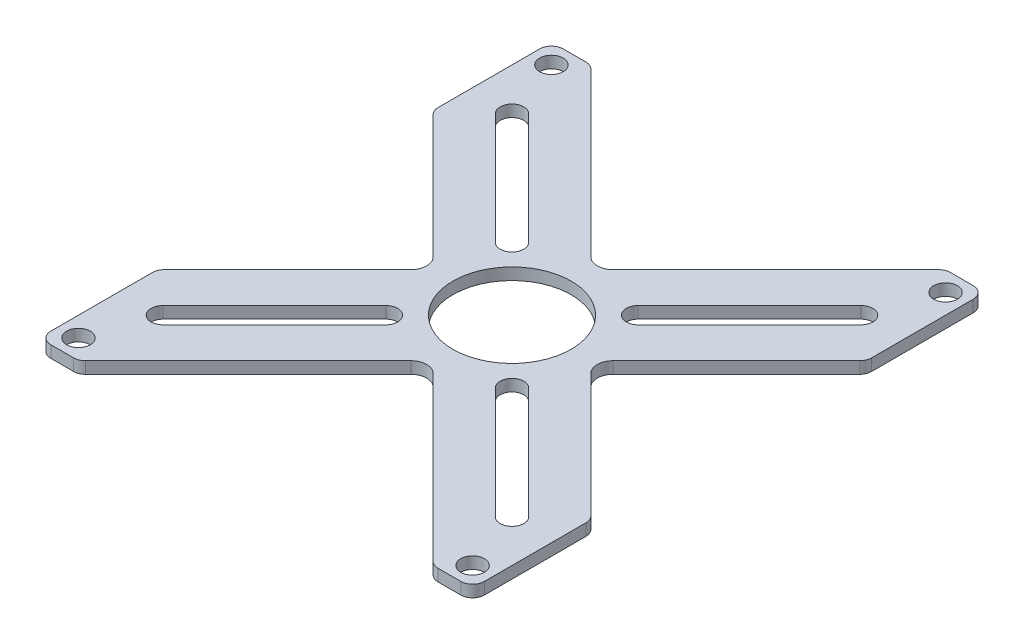
SolidWorks part; units mm, degrees
ref_plane "前视基准面" through (0, 0, 0) normal (0, 0, 1) x (1, 0, 0)
ref_plane "上视基准面" through (0, 0, 0) normal (0, 1, 0) x (1, 0, 0)
ref_plane "右视基准面" through (0, 0, 0) normal (1, 0, 0) x (0, 0, -1)
other "Configuration Table"
sketch "草图1" plane through (0, 0, 0) normal (0, 1, 0) x (1, 0, 0)
  line L1 (-27.5, -32.5) -> (27.5, -32.5)
  line L2 (-27.5, -32.5) -> (-27.5, 32.5)
  line L3 (-27.5, 32.5) -> (27.5, 32.5)
  line L4 (27.5, -32.5) -> (27.5, 32.5)
  line L5 (0, 32.5) -> (0, -32.5) construction
  line L6 (-27.5, 0) -> (27.5, 0) construction
  circle A0 centre (-25, 30) radius 1.5
  circle A1 centre (25, 30) radius 1.5
  circle A2 centre (25, -30) radius 1.5
  circle A3 centre (-25, -30) radius 1.5
  point P0 (0, 0)
  dimension "D3" = 3
  dimension "D4" = 3
  dimension "D5" = 3
  dimension "D6" = 3
  dimension "D7" = 25
  dimension "D8" = 25
  dimension "D9" = 30
  dimension "D10" = 30
  dimension "D11" = 25
  dimension "D12" = 25
  dimension "D13" = 30
  dimension "D14" = 30
  dimension "D1" = 65
  dimension "D2" = 55
extrude "凸台-拉伸1" add sketch "草图1" along normal blind 1.5
sketch "草图2" plane through (0, 1.5, 0) normal (0, 1, 0) x (1, 0, 0)
  line L0 (-22.1421, 22.1421) -> (-8, 8) construction
  line L1 (-21.0815, 23.2028) -> (-6.9393, 9.0607)
  line L2 (-23.2028, 21.0815) -> (-9.0607, 6.9393)
  line L3 (-27.5, 32.5) -> (-27.5, -32.5) construction
  line L4 (21.0815, 23.2028) -> (6.9393, 9.0607)
  line L5 (23.2028, 21.0815) -> (9.0607, 6.9393)
  line L6 (22.1421, 22.1421) -> (8, 8) construction
  line L7 (23.2028, -21.0815) -> (9.0607, -6.9393)
  line L8 (21.0815, -23.2028) -> (6.9393, -9.0607)
  line L9 (22.1421, -22.1421) -> (8, -8) construction
  line L10 (-21.0815, -23.2028) -> (-6.9393, -9.0607)
  line L11 (-23.2028, -21.0815) -> (-9.0607, -6.9393)
  line L12 (-22.1421, -22.1421) -> (-8, -8) construction
  arc A1 (-21.0815, 23.2028) -> (-23.2028, 21.0815) centre (-22.1421, 22.1421) ccw
  arc A2 (-9.0607, 6.9393) -> (-6.9393, 9.0607) centre (-8, 8) ccw
  arc A3 (23.2028, 21.0815) -> (21.0815, 23.2028) centre (22.1421, 22.1421) ccw
  arc A4 (6.9393, 9.0607) -> (9.0607, 6.9393) centre (8, 8) ccw
  arc A5 (21.0815, -23.2028) -> (23.2028, -21.0815) centre (22.1421, -22.1421) ccw
  arc A6 (9.0607, -6.9393) -> (6.9393, -9.0607) centre (8, -8) ccw
  arc A7 (-23.2028, -21.0815) -> (-21.0815, -23.2028) centre (-22.1421, -22.1421) ccw
  arc A8 (-6.9393, -9.0607) -> (-9.0607, -6.9393) centre (-8, -8) ccw
  point P2 (-15.0711, 15.0711)
  point P15 (15.0711, 15.0711)
  point P22 (15.0711, -15.0711)
  point P29 (-15.0711, -15.0711)
  point P34 (0, 0)
  dimension "D4" = 8
  dimension "D5" = 8
  dimension "D1" = 3
  dimension "D2" = 45
  dimension "D3" = 20
  dimension "D6" = 4
extrude "切除-拉伸1" cut sketch "草图2" against normal blind 1.5
sketch "草图3" plane through (0, 1.5, 0) normal (0, 1, 0) x (1, 0, 0)
  line L0 (-22.5, 32.5) -> (0, 10)
  line L1 (27.5, 32.5) -> (-27.5, 32.5) construction
  line L2 (0, 10) -> (22.5, 32.5)
  line L3 (22.5, 32.5) -> (-22.5, 32.5)
  line L4 (-27.5, 17.5) -> (-10, 0)
  line L5 (-27.5, 32.5) -> (-27.5, -32.5) construction
  line L6 (-10, 0) -> (-27.5, -17.5)
  line L7 (-27.5, -17.5) -> (-27.5, 17.5)
  line L8 (-1000, 0) -> (49000, 0) construction
  line L9 (0, -1000) -> (0, 49000) construction
  line L10 (10, 0) -> (27.5, -17.5)
  line L11 (27.5, 17.5) -> (10, 0)
  line L12 (27.5, -17.5) -> (27.5, 17.5)
  line L13 (0, -10) -> (22.5, -32.5)
  line L14 (-22.5, -32.5) -> (0, -10)
  line L15 (22.5, -32.5) -> (-22.5, -32.5)
  circle A0 centre (0, 0) radius 7.5
  dimension "D6" = 15
  dimension "D1" = 45
  dimension "D2" = 45
  dimension "D3" = 0
  dimension "D4" = 0
  dimension "D5" = 35
extrude "切除-拉伸2" cut sketch "草图3" against normal through all
fillet "圆角1" radius 2 4 edges at (0, 0.75, -10) (0, 0.75, 10) (10, 0.75, 0) (-10, 0.75, 0)
fillet "圆角2" radius 1.5 12 edges at (-27.5, 0.75, 17.5) (-27.5, 0.75, 32.5) (-22.5, 0.75, 32.5) (-27.5, 0.75, -17.5) (-27.5, 0.75, -32.5) (-22.5, 0.75, -32.5) (22.5, 0.75, -32.5) (27.5, 0.75, -32.5) (27.5, 0.75, -17.5) (27.5, 0.75, 17.5) (27.5, 0.75, 32.5) (22.5, 0.75, 32.5)
